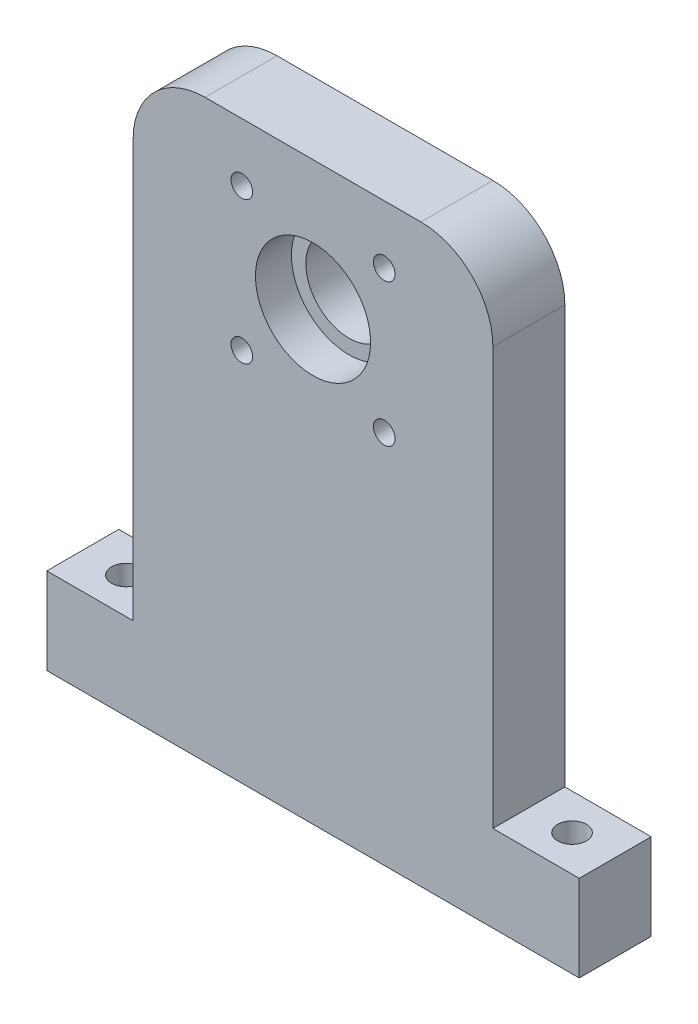
SolidWorks part; units mm, degrees
material "1060 Alloy"
ref_plane "Front Plane" through (0, 0, 0) normal (0, 0, 1) x (1, 0, 0)
ref_plane "Top Plane" through (0, 0, 0) normal (0, 1, 0) x (1, 0, 0)
ref_plane "Right Plane" through (0, 0, 0) normal (1, 0, 0) x (0, 0, -1)
sketch "Sketch1" plane through (0, 0, 0) normal (0, 0, 1) x (1, 0, 0)
  line L0 (-37.625, -24) -> (36.375, -24)
  line L1 (36.375, -24) -> (36.375, -12)
  line L2 (36.375, -12) -> (24.375, -12)
  line L3 (24.375, -12) -> (24.375, 56)
  line L4 (24.375, 56) -> (-25.625, 56)
  line L5 (-25.625, 56) -> (-25.625, -12)
  line L6 (-25.625, -12) -> (-37.625, -12)
  line L7 (-37.625, -12) -> (-37.625, -24)
  dimension "D1" = 12
  dimension "D2" = 12
  dimension "D3" = 12
  dimension "D4" = 12
  dimension "D5" = 68
  dimension "D6" = 50
extrude "Boss-Extrude1" add sketch "Sketch1" along normal blind 10 contours L5 L6 L7 L0 L1 L2 L3 L4
sketch "Sketch2" plane through (0, 0, 10) normal (0, 0, 1) x (1, 0, 0)
  line L0 (-37.625, -24) -> (36.375, -24) construction
  line L1 (24.375, -12) -> (24.375, 56) construction
  circle A0 centre (-0.625, 38) radius 8
  circle A1 centre (-0.625, 38) radius 5
  dimension "D1" = 16
  dimension "D4" = 10
  dimension "D2" = 62
  dimension "D3" = 25
extrude "Cut-Extrude1" cut sketch "Sketch2" against normal blind 5 contours A0
fillet "Fillet1" radius 10 2 edges at (-25.625, 56, 5) (24.375, 56, 5)
sketch "Sketch4" plane through (0, -12, 0) normal (0, 1, 0) x (1, 0, 0)
  line L0 (36.375, -10) -> (36.375, 0) construction
  line L1 (36.375, 0) -> (24.375, 0) construction
  circle A0 centre (30.375, -5) radius 2
  dimension "D1" = 4
  dimension "D2" = 6
  dimension "D3" = 5
extrude "Cut-Extrude3" cut sketch "Sketch4" against normal blind 21
sketch "Sketch5" plane through (0, -12, 0) normal (0, 1, 0) x (1, 0, 0)
  line L0 (-25.625, 0) -> (-37.625, 0) construction
  line L2 (-37.625, -10) -> (-37.625, 0) construction
  circle A0 centre (-31.625, -5) radius 2
  dimension "D1" = 4
  dimension "D2" = 5
  dimension "D3" = 6
extrude "Cut-Extrude4" cut sketch "Sketch5" against normal blind 25
sketch "Sketch6" plane through (0, 0, 10) normal (0, 0, 1) x (1, 0, 0)
  line L0 (-0.625, 38) -> (-0.625, 74.5939) construction
  line L1 (-0.625, 38) -> (18.2909, 56.9159) construction
  circle A0 centre (9.2745, 47.8995) radius 1.5
  dimension "D2" = 3
  dimension "D1" = 45
  dimension "D3" = 14
extrude "Cut-Extrude5" cut sketch "Sketch6" against normal blind 10
pattern_circular "CirPattern1" count 4 every 90 about axis through (-0.625, 38, 0) along (0, 0, 1) of "Cut-Extrude5"
sketch "Sketch8" plane through (0, 0, 10) normal (0, 0, 1) x (1, 0, 0)
  circle A0 centre (-0.625, 38) radius 6
  dimension "D1" = 12
extrude "Cut-Extrude8" cut sketch "Sketch8" against normal blind 10
